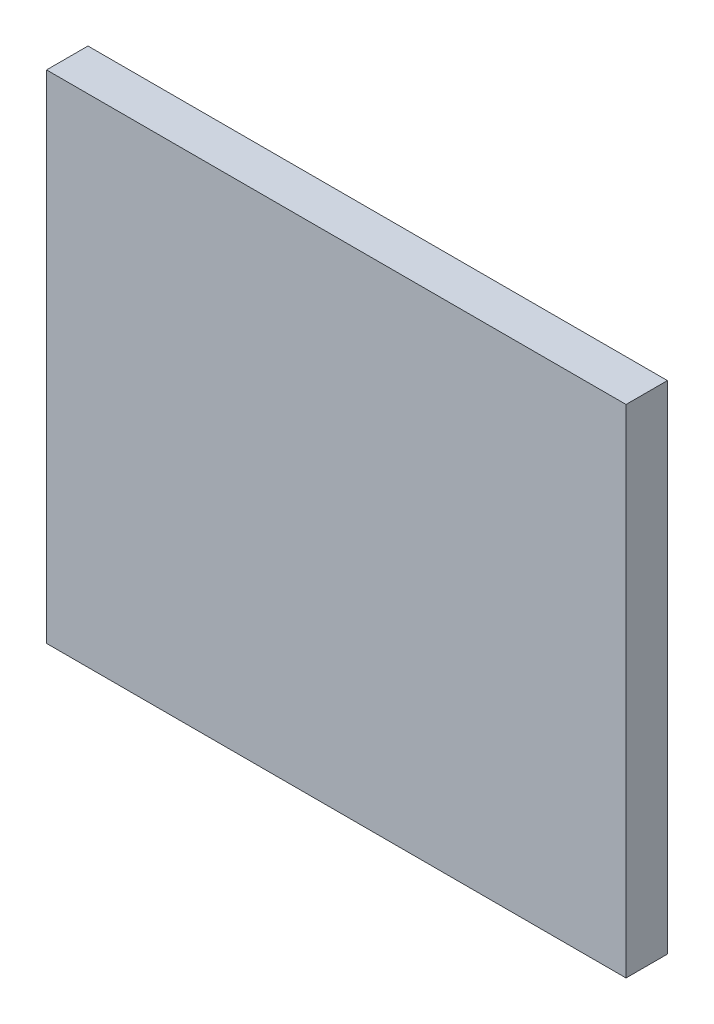
SolidWorks part; units mm, degrees
ref_plane "Front Plane" through (0, 0, 0) normal (0, 0, 1) x (1, 0, 0)
ref_plane "Top Plane" through (0, 0, 0) normal (0, 1, 0) x (1, 0, 0)
ref_plane "Right Plane" through (0, 0, 0) normal (1, 0, 0) x (0, 0, -1)
sketch "Sketch1" plane through (0, 0, 0) normal (0, 0, 1) x (1, 0, 0)
  line L1 (0, 0) -> (88.9, 0)
  line L2 (0, 0) -> (0, 76.2)
  line L3 (0, 76.2) -> (88.9, 76.2)
  line L4 (88.9, 0) -> (88.9, 76.2)
  dimension "D1" = 88.9
  dimension "D2" = 76.2
extrude "Boss-Extrude1" add sketch "Sketch1" along normal blind 6.35
